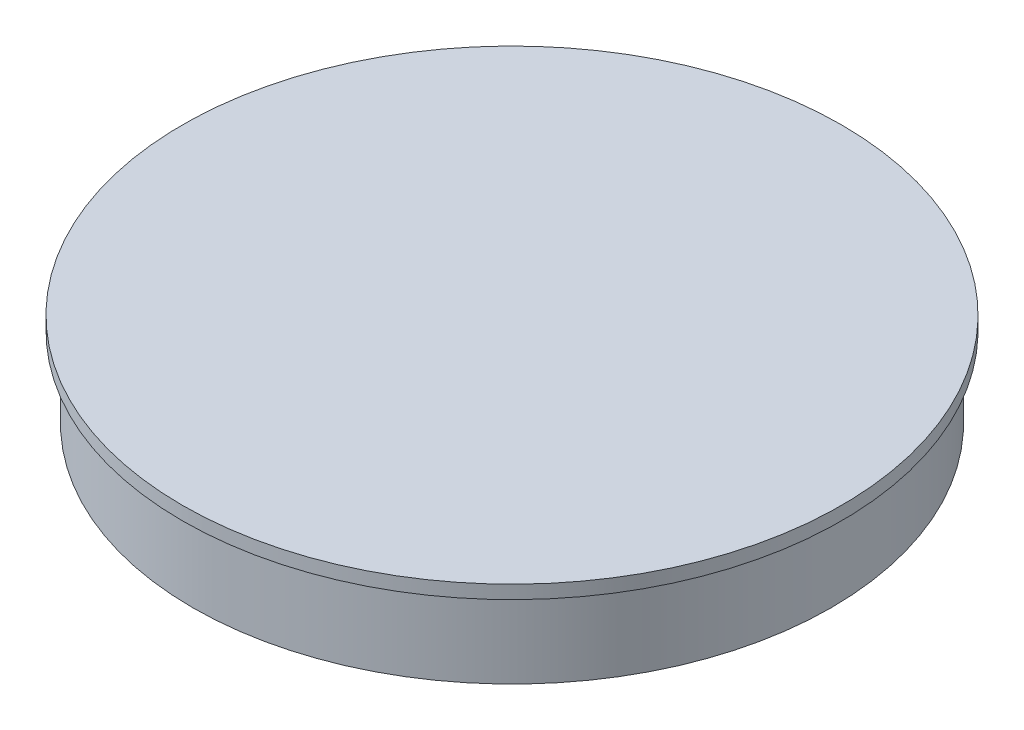
SolidWorks part; units mm, degrees
ref_plane "Front Plane" through (0, 0, 0) normal (0, 0, 1) x (1, 0, 0)
ref_plane "Top Plane" through (0, 0, 0) normal (0, 1, 0) x (1, 0, 0)
ref_plane "Right Plane" through (0, 0, 0) normal (1, 0, 0) x (0, 0, -1)
sketch "Sketch1" plane through (0, 0, 0) normal (0, 1, 0) x (1, 0, 0)
  circle A0 centre (0, 0) radius 35.75
  circle A1 centre (0, 0) radius 34.75
  dimension "D1" = 71.5
  dimension "D2" = 1
extrude "Boss-Extrude1" add sketch "Sketch1" along normal blind 9
sketch "Sketch2" plane through (0, 9, 0) normal (0, 1, 0) x (1, 0, 0)
  circle A0 centre (0, 0) radius 36.9
  dimension "D1" = 73.8
extrude "Boss-Extrude2" add sketch "Sketch2" along normal blind 1.5
